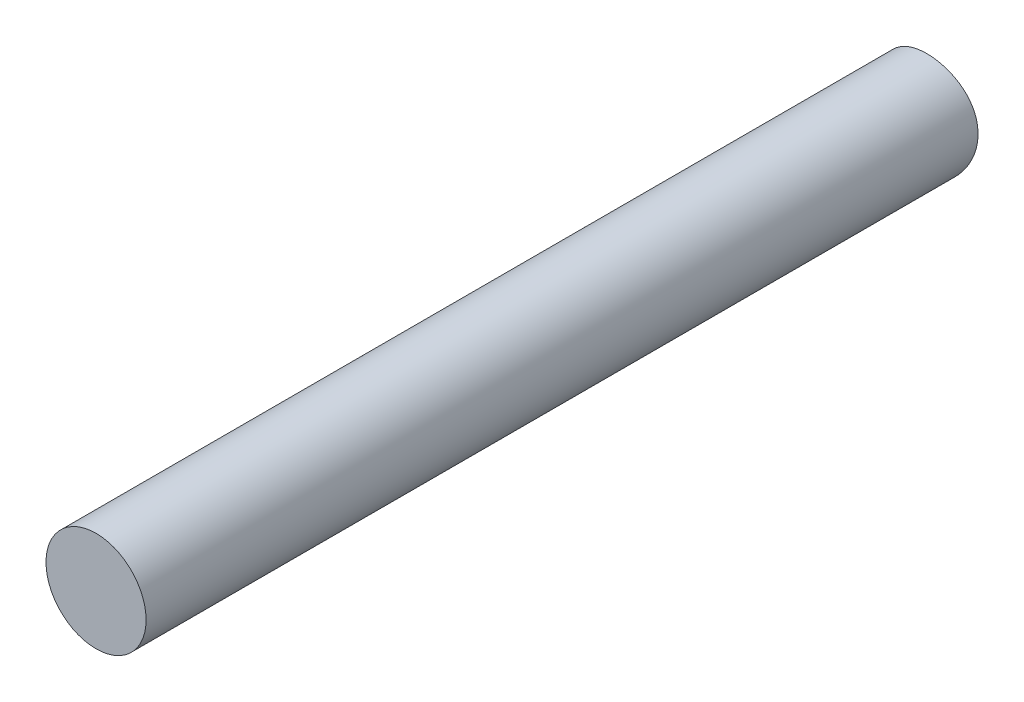
SolidWorks part; units mm, degrees
ref_plane "Front Plane" through (0, 0, 0) normal (0, 0, 1) x (1, 0, 0)
ref_plane "Top Plane" through (0, 0, 0) normal (0, 1, 0) x (1, 0, 0)
ref_plane "Right Plane" through (0, 0, 0) normal (1, 0, 0) x (0, 0, -1)
sketch "Sketch1" plane through (0, 0, 0) normal (0, 0, 1) x (1, 0, 0)
  circle A0 centre (0, 0) radius 6
  dimension "D1" = 12
extrude "Boss-Extrude1" add sketch "Sketch1" along normal blind 100
sketch "Sketch3" plane through (0, 0, 0) normal (0, 0, 1) x (1, 0, 0)
  line L0 (-5.9957, 6) -> (3.9129, 6) construction
  circle A0 centre (0, 0) radius 6 construction
ref_plane "Plane1" through (0, 5.9109, -0.7258) normal (0, 0.9925, -0.1219) x (1, 0, 0)
sketch "Sketch4" plane through (0, 5.9109, -0.7258) normal (0, 0.9925, -0.1219) x (1, 0, 0)
  line L0 (6, -99.2546) -> (6, 0) construction
  line L1 (-6, 0) -> (-6, -99.2546) construction
  line L2 (-6, -0.2782) -> (-6, 1.7377)
  line L3 (-6, 1.7377) -> (6, 1.7377)
  line L4 (6, 1.7377) -> (6, -0.2782)
  arc A0 (-6, -0.2782) -> (6, -0.2782) centre (0, 20.8878) ccw
  dimension "D1" = 22
sketch "Sketch2" plane through (0, 0, 0) normal (0, 1, 0) x (1, 0, 0)
  line L0 (-6, 0) -> (6, 0)
  arc A0 (-6, 0) -> (6, 0) centre (0, 21.166) ccw
  dimension "D1" = 22
extrude "Cut-Extrude3" cut sketch "Sketch4" against normal up to surface (5.7419 mm away)
sketch "Sketch5" plane through (0, 0, 0) normal (0, 1, 0) x (1, 0, 0)
  line L0 (-8.6246, 1.36) -> (-5.3035, 1.36) construction
